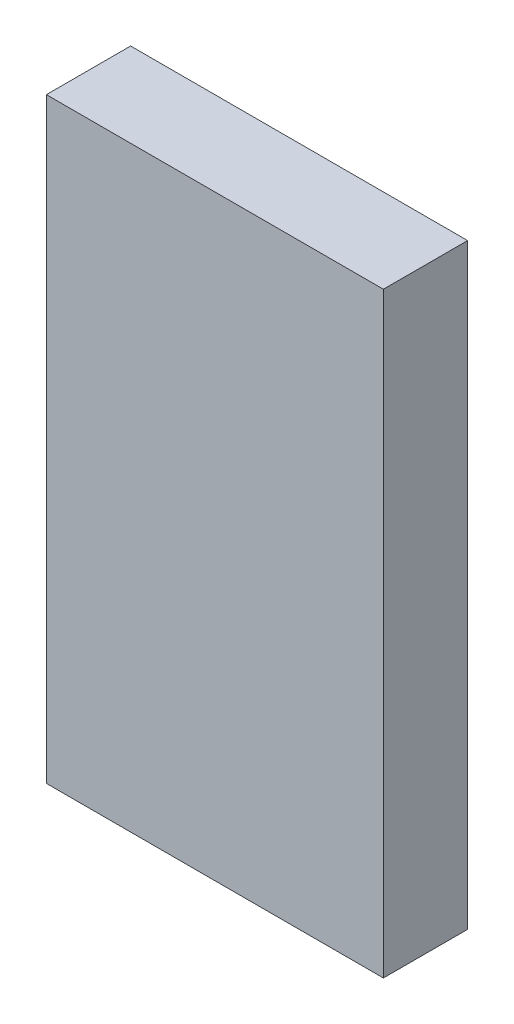
SolidWorks part; units mm, degrees
ref_plane "Front Plane" through (0, 0, 0) normal (0, 0, 1) x (1, 0, 0)
ref_plane "Top Plane" through (0, 0, 0) normal (0, 1, 0) x (1, 0, 0)
ref_plane "Right Plane" through (0, 0, 0) normal (1, 0, 0) x (0, 0, -1)
sketch "Sketch1" plane through (0, 0, 0) normal (0, 1, 0) x (1, 0, 0)
  line L1 (0, 0) -> (12.7, 0)
  line L2 (0, 0) -> (0, 3.175)
  line L3 (0, 3.175) -> (12.7, 3.175)
  line L4 (12.7, 0) -> (12.7, 3.175)
  dimension "D1" = 12.7
extrude "Boss-Extrude1" add sketch "Sketch1" along normal blind 22.479
